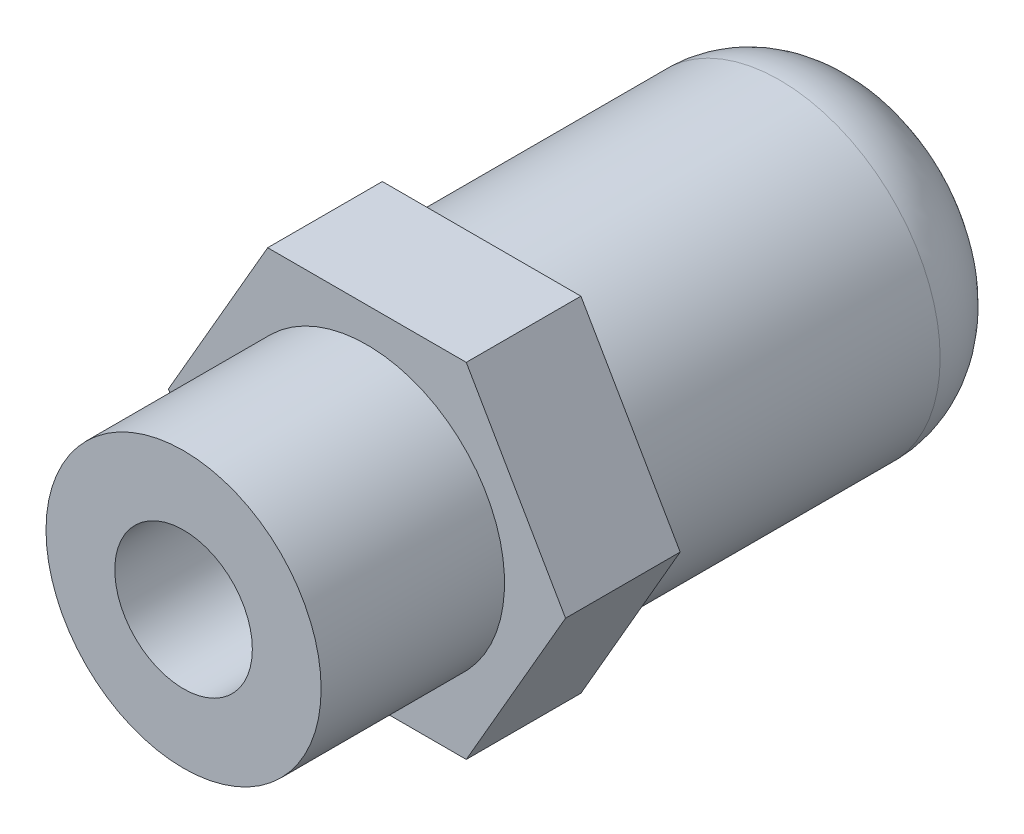
SolidWorks part; units mm, degrees
ref_plane "Přední" through (0, 0, 0) normal (0, 0, 1) x (1, 0, 0)
ref_plane "Horní" through (0, 0, 0) normal (0, 1, 0) x (1, 0, 0)
ref_plane "Pravá" through (0, 0, 0) normal (1, 0, 0) x (0, 0, -1)
sketch "Skica1" plane through (0, 0, 0) normal (0, 0, 1) x (1, 0, 0)
  circle A0 centre (0, 0) radius 6
  dimension "D1" = 12
extrude "Přidat vysunutím1" add sketch "Skica1" along normal blind 8
sketch "Skica2" plane through (0, 0, 0) normal (0, 0, -1) x (-1, 0, 0)
  line L1 (4.3301, -7.5) -> (8.6603, 0)
  line L2 (8.6603, 0) -> (4.3301, 7.5)
  line L3 (4.3301, 7.5) -> (-4.3301, 7.5)
  line L4 (-4.3301, 7.5) -> (-8.6603, 0)
  line L5 (-8.6603, 0) -> (-4.3301, -7.5)
  line L6 (-4.3301, -7.5) -> (4.3301, -7.5)
  circle A0 centre (0, 0) radius 7.5 construction
  dimension "D1" = 15
extrude "Přidat vysunutím2" add sketch "Skica2" along normal blind 5
sketch "Skica3" plane through (0, 0, -5) normal (0, 0, -1) x (-1, 0, 0)
  circle A0 centre (0, 0) radius 7
  dimension "D1" = 14
extrude "Přidat vysunutím3" add sketch "Skica3" along normal blind 17
fillet "Zaoblit1" radius 4 1 edges at (-7, 0, -22)
sketch "Skica4" plane through (0, 0, 8) normal (0, 0, 1) x (1, 0, 0)
  circle A0 centre (0, 0) radius 3
  dimension "D1" = 6
extrude "Odebrat vysunutím1" cut sketch "Skica4" against normal through all
